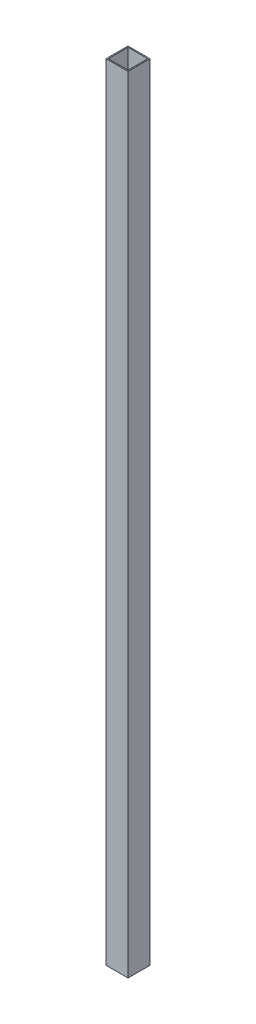
SolidWorks part; units mm, degrees
ref_plane "Front Plane" through (0, 0, 0) normal (0, 0, 1) x (1, 0, 0)
ref_plane "Top Plane" through (0, 0, 0) normal (0, 1, 0) x (1, 0, 0)
ref_plane "Right Plane" through (0, 0, 0) normal (1, 0, 0) x (0, 0, -1)
sketch "Sketch1" plane through (0, 0, 0) normal (0, 1, 0) x (1, 0, 0)
  line L1 (-9, 9) -> (9, 9)
  line L2 (-9, 9) -> (-9, -9)
  line L3 (-9, -9) -> (9, -9)
  line L4 (9, 9) -> (9, -9)
  line L5 (-9, 9) -> (9, -9) construction
  line L6 (-9, -9) -> (9, 9) construction
  line L7 (-10, 10) -> (10, 10)
  line L8 (-10, 10) -> (-10, -10)
  line L9 (-10, -10) -> (10, -10)
  line L10 (10, 10) -> (10, -10)
  line L11 (-10, 10) -> (10, -10) construction
  line L12 (-10, -10) -> (10, 10) construction
  point P0 (0, 0)
  point P6 (0, 0)
  dimension "D1" = 20
  dimension "D2" = 20
  dimension "D3" = 18
  dimension "D4" = 18
extrude "Boss-Extrude1" add sketch "Sketch1" along normal blind 715.05
